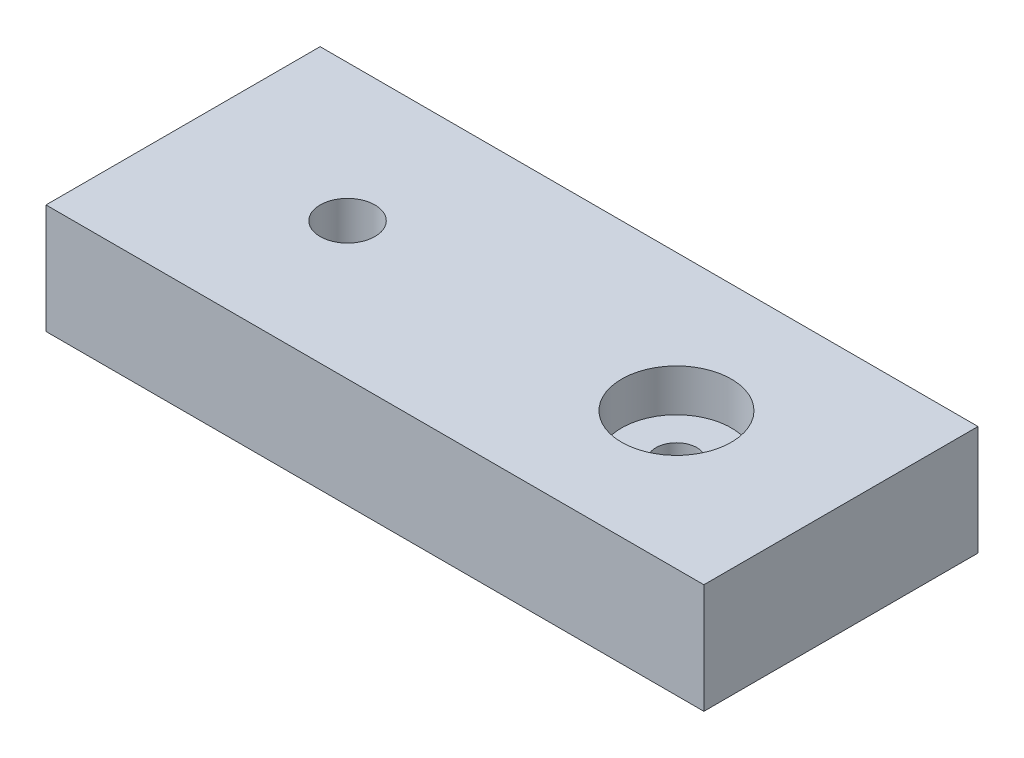
SolidWorks part; units mm, degrees
ref_plane "Front Plane" through (0, 0, 0) normal (0, 0, 1) x (1, 0, 0)
ref_plane "Top Plane" through (0, 0, 0) normal (0, 1, 0) x (1, 0, 0)
ref_plane "Right Plane" through (0, 0, 0) normal (1, 0, 0) x (0, 0, -1)
sketch "Sketch1" plane through (0, 0, 0) normal (0, 1, 0) x (1, 0, 0)
  line L1 (-38.1, -15.875) -> (38.1, -15.875)
  line L2 (-38.1, -15.875) -> (-38.1, 15.875)
  line L3 (-38.1, 15.875) -> (38.1, 15.875)
  line L4 (38.1, -15.875) -> (38.1, 15.875)
  line L5 (-38.1, -15.875) -> (38.1, 15.875) construction
  line L6 (-38.1, 15.875) -> (38.1, -15.875) construction
  point P0 (0, 0)
  dimension "D1" = 76.2
  dimension "D2" = 31.75
extrude "Boss-Extrude1" add sketch "Sketch1" along normal blind 12.7
sketch "Sketch2" plane through (0, 12.7, 0) normal (0, 1, 0) x (1, 0, 0)
  line L0 (0, 0) -> (-38.1, 0) construction
  line L1 (-38.1, 15.875) -> (-38.1, -15.875) construction
  line L2 (0, 0) -> (38.1, 0) construction
  line L3 (38.1, -15.875) -> (38.1, 15.875) construction
  circle A0 centre (-19.05, 0) radius 3.175
  circle A1 centre (19.05, 0) radius 2.3813
  dimension "D1" = 6.35
  dimension "D2" = 4.7625
extrude "Cut-Extrude1" cut sketch "Sketch2" against normal through all
sketch "Sketch3" plane through (0, 12.7, 0) normal (0, 1, 0) x (1, 0, 0)
  circle A0 centre (19.05, 0) radius 6.35
  dimension "D1" = 12.7
extrude "Cut-Extrude2" cut sketch "Sketch3" against normal blind 4.9022
